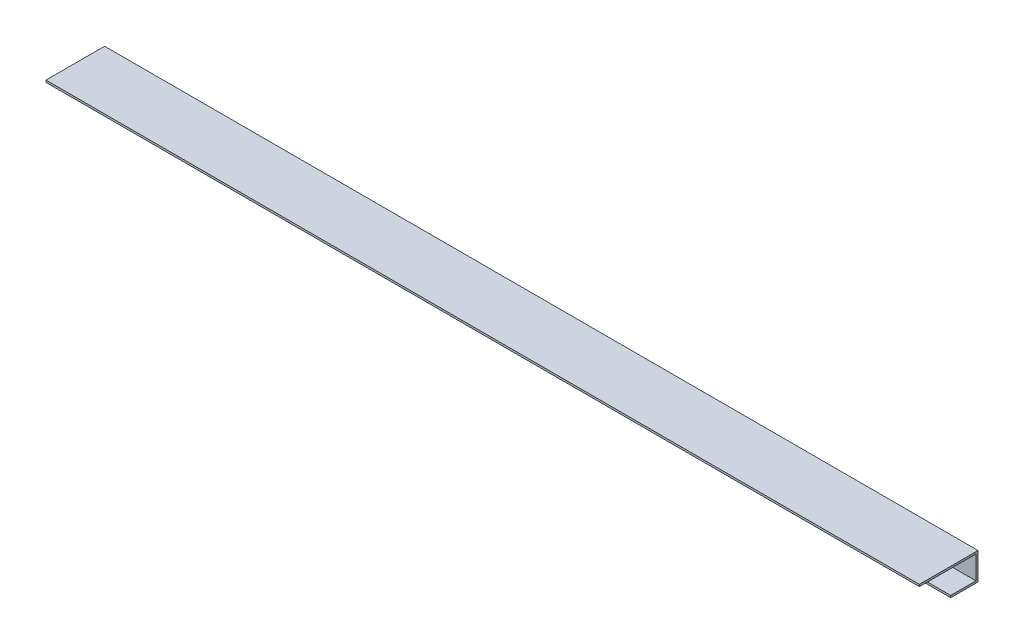
SolidWorks part; units mm, degrees
ref_plane "Front Plane" through (0, 0, 0) normal (0, 0, 1) x (1, 0, 0)
ref_plane "Top Plane" through (0, 0, 0) normal (0, 1, 0) x (1, 0, 0)
ref_plane "Right Plane" through (0, 0, 0) normal (1, 0, 0) x (0, 0, -1)
sketch "Sketch1" plane through (0, 0, 0) normal (1, 0, 0) x (0, 0, -1)
  line L0 (0, 0) -> (58, 0)
  line L1 (58, 0) -> (58, -27)
  line L2 (58, -27) -> (31, -27)
  line L3 (0, -2) -> (56, -2)
  line L4 (56, -2) -> (56, -25)
  line L5 (56, -25) -> (31, -25)
  line L6 (0, 0) -> (0, -2)
  line L7 (31, -25) -> (31, -27)
  dimension "D1" = 2
  dimension "D2" = 58
  dimension "D3" = 27
  dimension "D4" = 27
extrude "Boss-Extrude1" add sketch "Sketch1" along normal blind 864
equation "\"door_base_short7_BR_Single_width\"=864"
equation "\"D1@Boss-Extrude1\"=\"door_base_short7_BR_Single_width\""
equation "\"CarBeamWidth\"=700.0"
equation "\"WheelWidth\"=650.0"
equation "\"Wheel_FrontBoxDistance\"=1390.0"
equation "\"boxLength\"=5100.0"
equation "\"boxWidth\"=1930.0"
equation "\"MetalSheet_3mm_length\"=5030.0"
equation "\"MetalSheet_3mm_width\"=1923.0"
equation "\"MetalSheet_3mm_FloorCut_L_length\"=1764.0"
equation "\"MetalSheet_3mm_FloorCut_L_disdance\"=1665.0"
equation "\"MetalSheet_3mm_FloorCut_R_length\"=1764.0"
equation "\"MetalSheet_3mm_FloorCut_R_disdance\"=1665.0"
equation "\"indoorHeight\"=1940.0"
equation "\"indoorHeight_para\"=25.0"
equation "\"rearLightHeight_para\"=265.0"
equation "\"haveDoor_R\"=1"
equation "\"side_door_bottom_R_3mm_length\"=1934.0"
equation "\"side_door_bottom_R_3mm_toFrontDistance\"=1583.0"
equation "\"1Bar_Side_RF_3mm_length\"=1493.0"
equation "\"1Bar_Side_RB_3mm_length\"=1493.0"
equation "\"DoorSeparator_RF_3mm_withHinge_toFrontDistance\"=1673.0"
equation "\"DoorSeparator_RF_3mm_withHinge_exist\"=1"
equation "\"DoorSeparator_RB_3mm_withHinge_toFrontDistance\"=3427.0"
equation "\"DoorSeparator_RB_3mm_withHinge_exist\"=1"
equation "\"Door_R1_L_open_Single_toFrontDistance\"=2547.5"
equation "\"Door_R1_L_open_Single_exist\"=1"
equation "\"door_base_long7_R1_L_open_Single_height\"=1890.0"
equation "\"door_base_short7_R1_L_open_Single_height\"=1890.0"
equation "\"door_base_short7_R1_L_open_Single_width\"=864"
equation "\"Door_R1_R_open_Single_toFrontDistance\"=3422.0"
equation "\"Door_R1_R_open_Single_exist\"=1"
equation "\"door_base_long7_R1_R_open_Single_height\"=1890.0"
equation "\"door_base_short7_R1_R_open_Single_height\"=1890.0"
equation "\"door_base_short7_R1_R_open_Single_width\"=864"
equation "\"x\"=66.0"
equation "\"door_base_double_BL_height\"=1890.0"
equation "\"door_base_short7_BL_Single_height\"=1890.0"
equation "\"door_base_short7_BL_Single_width\"=864"
equation "\"door_base_long7_BR_Single_height\"=1890.0"
equation "\"door_base_short7_BR_Single_height\"=1890.0"
equation "\"da\"=62.0"
equation "\"SquareTube_length\"=1923.0"
equation "\"channelSteel_length\"=5030.0"
equation "\"SquareTube_inFront_AvgDistance\"=285.0"
equation "\"SquareTube_inFront_TotalCount\"=5"
equation "\"SquareTube_inFront1_cutDepth50_R\"=0.5"
equation "\"SquareTube_inFront1_cutDepth50_L\"=0.5"
equation "\"SquareTube_inFront2_cutDepth50_R\"=0.5"
equation "\"SquareTube_inFront2_cutDepth50_L\"=0.5"
equation "\"SquareTube_inFront3_cutDepth50_R\"=0.5"
equation "\"SquareTube_inFront3_cutDepth50_L\"=0.5"
equation "\"SquareTube_inFront4_cutDepth50_R\"=0.5"
equation "\"SquareTube_inFront4_cutDepth50_L\"=0.5"
equation "\"SquareTube_inFront5_cutDepth50_R\"=50"
equation "\"SquareTube_inFront5_cutDepth50_L\"=50"
equation "\"SquareTube_inFront6_cutDepth50_R\"=50"
equation "\"SquareTube_inFront6_cutDepth50_L\"=50"
equation "\"SquareTube_inFront7_cutDepth50_R\"=50"
equation "\"SquareTube_inFront7_cutDepth50_L\"=50"
equation "\"SquareTube_inFront8_cutDepth50_R\"=50"
equation "\"SquareTube_inFront8_cutDepth50_L\"=50"
equation "\"SquareTube_inFront9_cutDepth50_R\"=50"
equation "\"SquareTube_inFront9_cutDepth50_L\"=50"
equation "\"SquareTube_inFront10_cutDepth50_R\"=50"
equation "\"SquareTube_inFront10_cutDepth50_L\"=50"
equation "\"SquareTube_inFront11_cutDepth50_R\"=50"
equation "\"SquareTube_inFront11_cutDepth50_L\"=50"
equation "\"SquareTube_inFront12_cutDepth50_R\"=50"
equation "\"SquareTube_inFront12_cutDepth50_L\"=50"
equation "\"SquareTube_inFront13_cutDepth50_R\"=50"
equation "\"SquareTube_inFront13_cutDepth50_L\"=50"
equation "\"SquareTube_inFront14_cutDepth50_R\"=50"
equation "\"SquareTube_inFront14_cutDepth50_L\"=50"
equation "\"SquareTube_inBack_AvgDistance\"=333.125"
equation "\"SquareTube_inBack_TotalCount\"=9"
equation "\"SquareTube_inBack1_cutDepth50_R\"=50"
equation "\"SquareTube_inBack1_cutDepth50_L\"=50"
equation "\"SquareTube_inBack2_cutDepth50_R\"=50"
equation "\"SquareTube_inBack2_cutDepth50_L\"=50"
equation "\"SquareTube_inBack3_cutDepth50_R\"=50"
equation "\"SquareTube_inBack3_cutDepth50_L\"=50"
equation "\"SquareTube_inBack4_cutDepth50_R\"=50"
equation "\"SquareTube_inBack4_cutDepth50_L\"=50"
equation "\"SquareTube_inBack5_cutDepth50_R\"=50"
equation "\"SquareTube_inBack5_cutDepth50_L\"=50"
equation "\"SquareTube_inBack6_cutDepth50_R\"=0.5"
equation "\"SquareTube_inBack6_cutDepth50_L\"=0.5"
equation "\"SquareTube_inBack7_cutDepth50_R\"=0.5"
equation "\"SquareTube_inBack7_cutDepth50_L\"=0.5"
equation "\"SquareTube_inBack8_cutDepth50_R\"=0.5"
equation "\"SquareTube_inBack8_cutDepth50_L\"=0.5"
